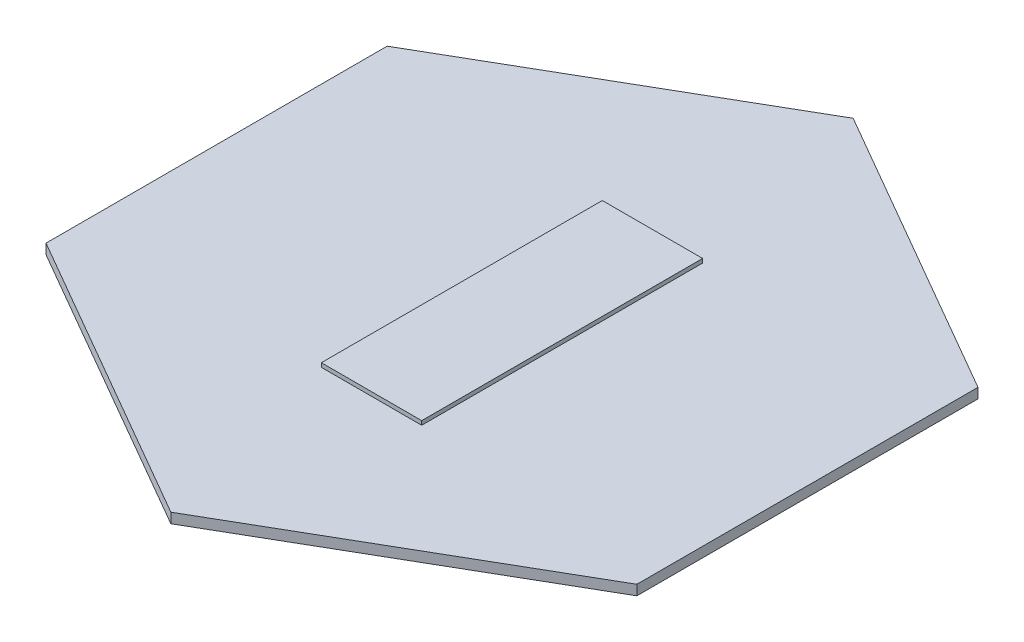
SolidWorks part; units mm, degrees
ref_plane "Front" through (0, 0, 0) normal (0, 0, 1) x (1, 0, 0)
ref_plane "Top" through (0, 0, 0) normal (0, 1, 0) x (1, 0, 0)
ref_plane "Right" through (0, 0, 0) normal (1, 0, 0) x (0, 0, -1)
sketch "Sketch1" plane through (0, 0, 0) normal (0, 1, 0) x (1, 0, 0)
  line L1 (73.6122, 42.5) -> (0, 85)
  line L2 (0, 85) -> (-73.6122, 42.5)
  line L3 (-73.6122, 42.5) -> (-73.6122, -42.5)
  line L4 (-73.6122, -42.5) -> (0, -85)
  line L5 (0, -85) -> (73.6122, -42.5)
  line L6 (73.6122, -42.5) -> (73.6122, 42.5)
  circle A0 centre (0, 0) radius 73.6122 construction
  dimension "D1" = 85
extrude "Boss-Extrude1" add sketch "Sketch1" along normal blind 2.5
sketch "Sketch2" plane through (0, 2.5, 0) normal (0, 1, 0) x (1, 0, 0)
  line L0 (-73.6122, 42.5) -> (-73.6122, -42.5) construction
  line L1 (-12.5, -35) -> (12.5, -35)
  line L2 (-12.5, -35) -> (-12.5, 35)
  line L3 (-12.5, 35) -> (12.5, 35)
  line L4 (12.5, -35) -> (12.5, 35)
  line L5 (-12.5, -35) -> (12.5, 35) construction
  line L6 (-12.5, 35) -> (12.5, -35) construction
  point P0 (0, 0)
  dimension "D1" = 70
  dimension "D2" = 25
extrude "Boss-Extrude2" add sketch "Sketch2" along normal blind 1
